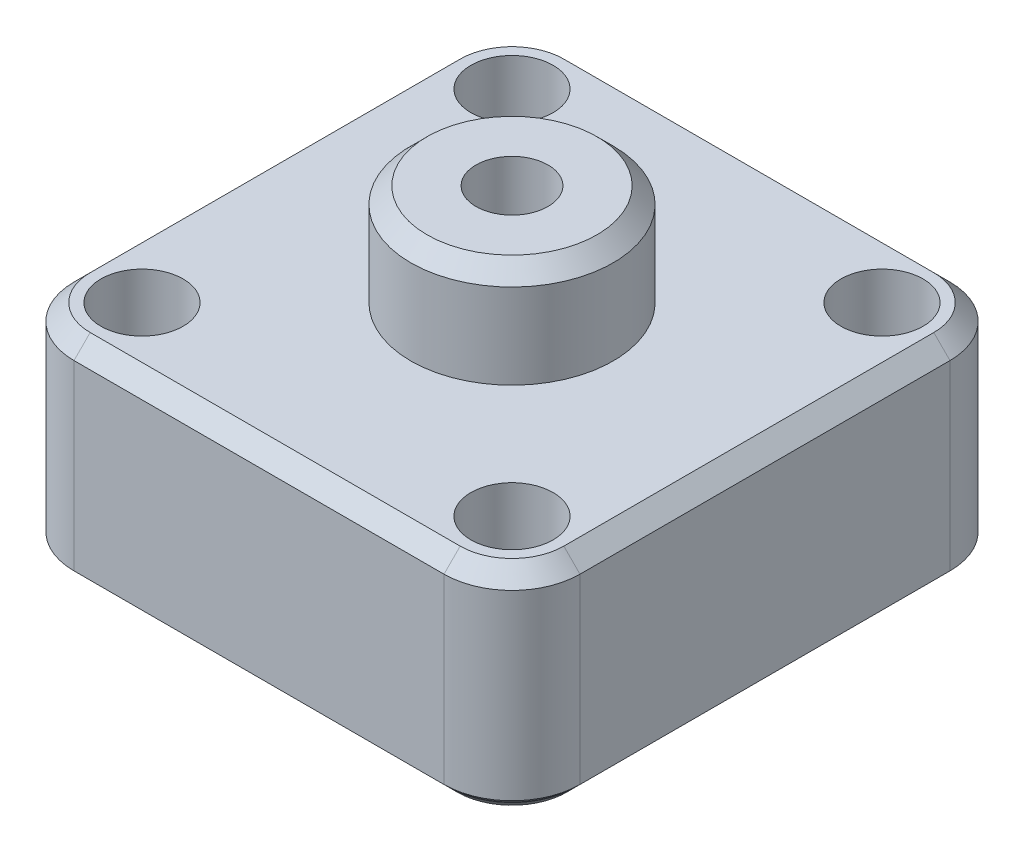
SolidWorks part; units mm, degrees
ref_plane "Front Plane" through (0, 0, 0) normal (0, 0, 1) x (1, 0, 0)
ref_plane "Top Plane" through (0, 0, 0) normal (0, 1, 0) x (1, 0, 0)
ref_plane "Right Plane" through (0, 0, 0) normal (1, 0, 0) x (0, 0, -1)
sketch "Sketch1" plane through (0, 0, 0) normal (0, 1, 0) x (1, 0, 0)
  line L1 (-7.9375, 7.9375) -> (7.9375, 7.9375)
  line L2 (-7.9375, 7.9375) -> (-7.9375, -7.9375)
  line L3 (-7.9375, -7.9375) -> (7.9375, -7.9375)
  line L4 (7.9375, 7.9375) -> (7.9375, -7.9375)
  line L5 (-7.9375, 7.9375) -> (7.9375, -7.9375) construction
  line L6 (-7.9375, -7.9375) -> (7.9375, 7.9375) construction
  point P0 (0, 0)
  dimension "D1" = 15.875
  dimension "D2" = 15.875
extrude "Boss-Extrude1" add sketch "Sketch1" along normal blind 9.525
hole_wizard "#5-40 Tapped Hole1" positions "Sketch2" profile "Sketch3" tap size "#5-40" standard "ANSI Inch" end condition through all
sketch "Sketch2" plane through (0, 0, 0) normal (0, -1, 0) x (-1, 0, 0)
  line L0 (-5.8039, 5.8039) -> (5.8039, -5.8039) construction
  point P0 (-5.8039, -5.8039)
  point P2 (-5.8039, 5.8039)
  point P4 (5.8039, 5.8039)
  point P6 (5.8039, -5.8039)
  point P13 (0, 0)
  point P14 (0, 0)
  point P15 (0, 0)
  point P16 (0, 0)
  dimension "D1" = 11.6078
  dimension "D2" = 11.6078
sketch "Sketch3" plane through (5.8039, 0, 5.8039) normal (1, 0, 0) x (0, 0, -1)
  line L0 (0, 0) -> (0, 9.525)
  line L1 (0, 9.525) -> (1.289, 9.525)
  line L2 (1.289, 9.525) -> (1.289, 0)
  line L5 (1.289, 0) -> (0, 0)
  line L11 (0, -6.35) -> (0, 107.95) construction
  dimension "Thru Tap Drill Dia." = 2.5781
  dimension "Thru Tap Drill Depth" = 9.525
cosmetic thread "Hole Thread1" parameters "D2"=3.175
cosmetic thread "Hole Thread2" parameters "D2"=3.175
cosmetic thread "Hole Thread3" parameters "D2"=3.175
cosmetic thread "Hole Thread4" parameters "D2"=3.175
sketch "Sketch4" plane through (0, 0, 0) normal (0, -1, 0) x (1, 0, 0)
  circle A0 centre (0, 0) radius 3.937
  dimension "D1" = 7.874
extrude "Boss-Extrude2" add sketch "Sketch4" along normal blind 1.143
sketch "Sketch10" plane through (0, -1.143, 0) normal (0, -1, 0) x (1, 0, 0)
  circle A0 centre (0, 0) radius 1.9685
  dimension "D1" = 3.937
extrude "Boss-Extrude4" add sketch "Sketch10" along normal offset from surface (4.953 mm away) 6.096 up to face at (0, 0, 3.937) offset beyond the face yes
hole_wizard "#4-40 Tapped Hole1" positions "Sketch5" profile "Sketch6" tap size "#4-40" standard "ANSI Inch" end condition through all
sketch "Sketch5" plane through (0, -6.096, 0) normal (0, -1, 0) x (-1, 0, 0)
  point P0 (0, 0)
sketch "Sketch6" plane through (0, -6.096, 0) normal (1, 0, 0) x (0, 0, -1)
  line L0 (0, 0) -> (0, 15.621)
  line L1 (0, 15.621) -> (1.1303, 15.621)
  line L2 (1.1303, 15.621) -> (1.1303, 0)
  line L5 (1.1303, 0) -> (0, 0)
  line L11 (0, -6.35) -> (0, 107.95) construction
  dimension "Thru Tap Drill Dia." = 2.2606
  dimension "Thru Tap Drill Depth" = 15.621
cosmetic thread "Hole Thread6" parameters "D2"=2.8448
sketch "Sketch8" plane through (0, 9.525, 0) normal (0, 1, 0) x (1, 0, 0)
  arc A0 (-3.8971, 8.3426) -> (-8.3426, 3.8971) centre (-5.8039, 5.8039) ccw
  arc A1 (8.3426, 3.8971) -> (3.8971, 8.3426) centre (5.8039, 5.8039) ccw
  arc A2 (3.8971, -8.3426) -> (8.3426, -3.8971) centre (5.8039, -5.8039) ccw
  arc A3 (-8.3426, -3.8971) -> (-3.8971, -8.3426) centre (-5.8039, -5.8039) ccw
  arc A4 (-3.8971, 8.3426) -> (3.8971, 8.3426) centre (0, 13.5311) ccw
  arc A5 (-8.3426, -3.8971) -> (-8.3426, 3.8971) centre (-13.5311, 0) ccw
  arc A6 (8.3426, 3.8971) -> (8.3426, -3.8971) centre (13.5311, 0) ccw
  arc A7 (3.8971, -8.3426) -> (-3.8971, -8.3426) centre (0, -13.5311) ccw
  point P1 (-14.204, 0)
  dimension "D1" = 3.175
extrude "Cut-Extrude2" [suppressed] cut sketch "Sketch8" against normal through all flip side to cut
sketch "Sketch9" plane through (0, 9.525, 0) normal (0, 1, 0) x (1, 0, 0)
  circle A0 centre (0, 0) radius 3.175
  dimension "D1" = 6.35
extrude "Cut-Extrude3" cut sketch "Sketch9" against normal offset from surface (3.175 mm away) 6.35 flip side to cut up to face at (0, 0, 3.937)
sketch "Sketch11" plane through (0, 0, 0) normal (0, -1, 0) x (1, 0, 0)
  line L0 (-5.8039, 7.9375) -> (5.8039, 7.9375)
  line L1 (7.9375, 5.8039) -> (7.9375, -5.8039)
  line L2 (5.8039, -7.9375) -> (-5.8039, -7.9375)
  line L3 (-7.9375, 5.8039) -> (-7.9375, -5.8039)
  line L4 (7.9375, 7.9375) -> (7.9375, -7.9375) construction
  arc A0 (7.9375, 5.8039) -> (5.8039, 7.9375) centre (5.8039, 5.8039) ccw
  arc A1 (-5.8039, 7.9375) -> (-7.9375, 5.8039) centre (-5.8039, 5.8039) ccw
  arc A2 (-7.9375, -5.8039) -> (-5.8039, -7.9375) centre (-5.8039, -5.8039) ccw
  arc A3 (5.8039, -7.9375) -> (7.9375, -5.8039) centre (5.8039, -5.8039) ccw
extrude "Cut-Extrude4" cut sketch "Sketch11" against normal through all flip side to cut
chamfer "Chamfer1" distance 0.254 angle 45 2 edges at (0, -1.143, -3.937) (0, -6.096, 1.9685)
chamfer "Chamfer3" distance 0.508 angle 45 9 edges at (7.9375, 6.35, 0) (7.3126, 6.35, -7.3126) (7.3126, 6.35, 7.3126) (0, 6.35, -7.9375) (0, 6.35, 7.9375) (-7.3126, 6.35, -7.3126) (-7.3126, 6.35, 7.3126) (-7.9375, 6.35, 0) (0, 9.525, 3.175)
chamfer "Chamfer4" distance 0.127 angle 45 8 edges at (-7.9375, 0, 0) (-7.3126, 0, 7.3126) (-7.3126, 0, -7.3126) (0, 0, 7.9375) (0, 0, -7.9375) (7.3126, 0, 7.3126) (7.3126, 0, -7.3126) (7.9375, 0, 0)
